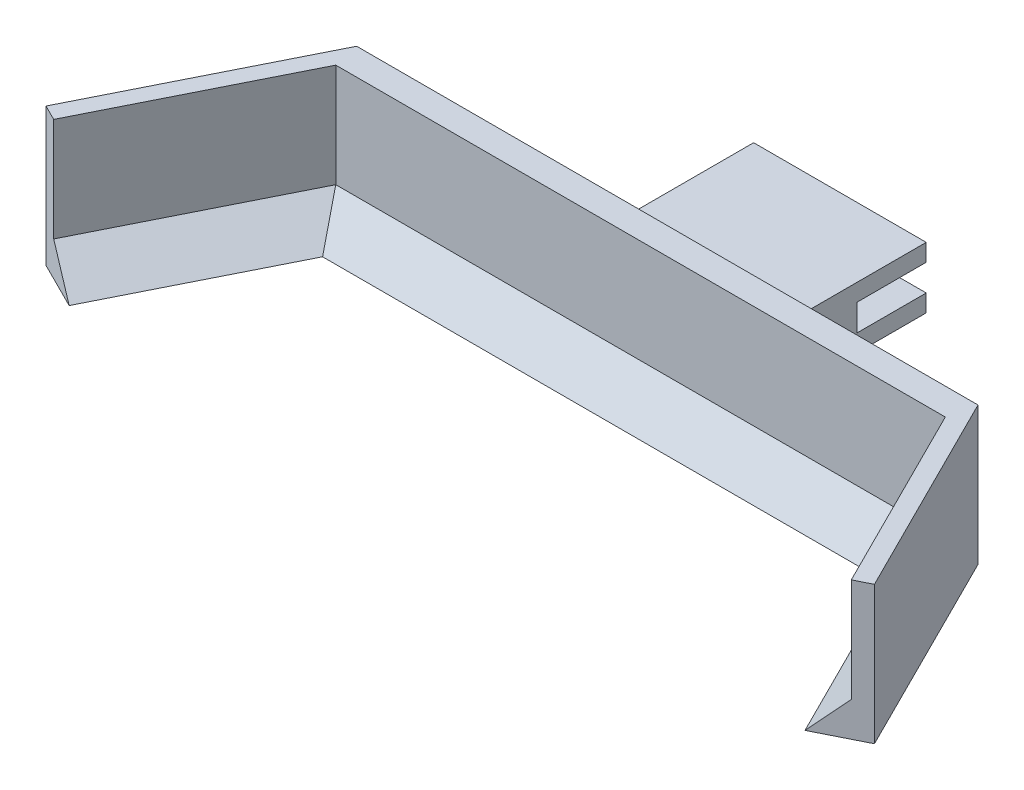
SolidWorks part; units mm, degrees
ref_plane "Front Plane" through (0, 0, 0) normal (0, 0, 1) x (1, 0, 0)
ref_plane "Top Plane" through (0, 0, 0) normal (0, 1, 0) x (1, 0, 0)
ref_plane "Right Plane" through (0, 0, 0) normal (1, 0, 0) x (0, 0, -1)
sketch "Sketch2" plane through (0, 0, 0) normal (0, 1, 0) x (1, 0, 0)
  line L0 (90, 5) -> (120, 5) construction
  line L1 (-90, 5) -> (90, 5)
  line L7 (-90, 5) -> (-120, 5) construction
  line L8 (-120, 5) -> (-120, -55) construction
  line L9 (-90, 5) -> (-120, -55)
  line L10 (-88.2918, -2.7639) -> (-115.5279, -57.2361)
  line L11 (-120, -55) -> (-115.5279, -57.2361)
  line L12 (-88.2918, -2.7639) -> (88.2918, -2.7639)
  line L13 (-85.5279, 2.7639) -> (-115.5279, -57.2361) construction
  line L14 (120, 5) -> (120, -55) construction
  line L15 (90, 5) -> (120, -55)
  line L16 (88.2918, -2.7639) -> (115.5279, -57.2361)
  line L17 (115.5279, -57.2361) -> (120, -55)
  line L18 (85.5279, 2.7639) -> (115.5279, -57.2361) construction
  point P0 (0, 0)
  dimension "D1" = 180
  dimension "D3" = 30
  dimension "D4" = 30
  dimension "D5" = 60
  dimension "D7" = 60
  dimension "D6" = 5
  dimension "D8" = 5
extrude "Boss-Extrude1" add sketch "Sketch2" along normal blind 10
draft "Draft1" type of draft neutral plane draft angle 45 faces to draft 3 face at (101.9098, 5, 30) face at (0, 5, 2.7639) face at (-101.9098, 5, 30) neutral plane through (0, 10, 0) neutral plane normal (0, 1, 0) parameters "D1"=45
sketch "Sketch5" plane through (0, 10, 0) normal (0, 1, 0) x (1, 0, 0)
  line L0 (-120, -55) -> (-90, 5)
  line L1 (-90, 5) -> (90, 5)
  line L2 (90, 5) -> (120, -55)
  line L3 (120, -55) -> (115.5279, -57.2361)
  line L4 (115.5279, -57.2361) -> (88.2918, -2.7639)
  line L5 (88.2918, -2.7639) -> (-88.2918, -2.7639)
  line L6 (-88.2918, -2.7639) -> (-115.5279, -57.2361)
  line L7 (-115.5279, -57.2361) -> (-120, -55)
extrude "Boss-Extrude2" add sketch "Sketch5" along normal blind 30
sketch "Sketch6" plane through (0, 0, -5) normal (0, 0, -1) x (-1, 0, 0)
  line L0 (0, 0) -> (0, 14.45) construction
  line L2 (-25, 5.6) -> (25, 5.6)
  line L3 (-25, 5.6) -> (-25, 23.3)
  line L4 (-25, 23.3) -> (25, 23.3)
  line L5 (25, 5.6) -> (25, 23.3)
  line L6 (-25, 5.6) -> (25, 23.3) construction
  line L7 (-25, 23.3) -> (25, 5.6) construction
  point P5 (0, 14.45)
  dimension "D1" = 50
  dimension "D2" = 17.7
  dimension "D3" = 14.45
extrude "Boss-Extrude3" add sketch "Sketch6" along normal blind 50
sketch "Sketch7" plane through (0, 0, -55) normal (0, 0, -1) x (-1, 0, 0)
  line L0 (-25, 5.6) -> (-25, 10.6) construction
  line L1 (-25, 23.3) -> (-25, 5.6) construction
  line L2 (25, 5.6) -> (25, 23.3) construction
  line L3 (-25, 10.6) -> (25, 10.6)
  line L4 (-25, 10.6) -> (-25, 18.3)
  line L5 (-25, 18.3) -> (25, 18.3)
  line L6 (25, 10.6) -> (25, 18.3)
  dimension "D1" = 5
  dimension "D2" = 7.7
extrude "Cut-Extrude4" cut sketch "Sketch7" against normal blind 20
